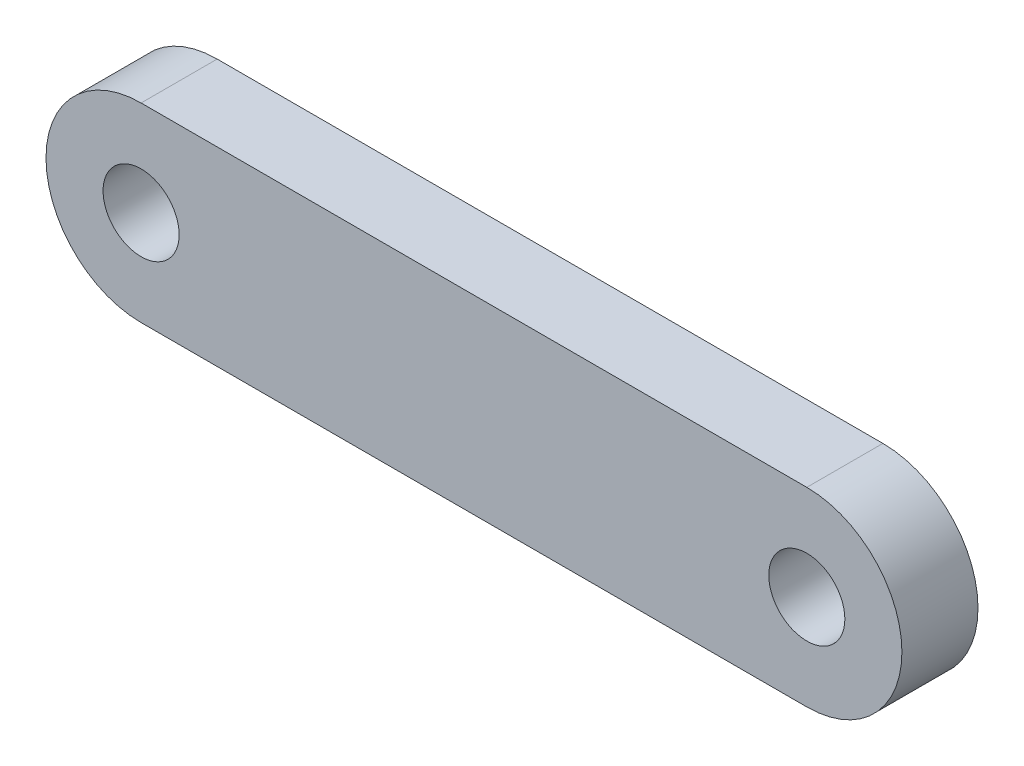
SolidWorks part; units mm, degrees
ref_plane "Front Plane" through (0, 0, 0) normal (0, 0, 1) x (1, 0, 0)
ref_plane "Top Plane" through (0, 0, 0) normal (0, 1, 0) x (1, 0, 0)
ref_plane "Right Plane" through (0, 0, 0) normal (1, 0, 0) x (0, 0, -1)
sketch "Sketch1" plane through (0, 0, 0) normal (0, 0, 1) x (1, 0, 0)
  line L0 (-35, 0) -> (0, 0) construction
  line L1 (-35, 5) -> (0, 5)
  line L2 (-35, -5) -> (0, -5)
  arc A0 (-35, 5) -> (-35, -5) centre (-35, 0) ccw
  arc A1 (0, -5) -> (0, 5) centre (0, 0) ccw
  circle A2 centre (-35, 0) radius 2
  circle A3 centre (0, 0) radius 2
  point P3 (-17.5, 0)
  point P12 (0, 0)
  dimension "D1" = 35
  dimension "D2" = 5
  dimension "D3" = 4
extrude "Boss-Extrude1" add sketch "Sketch1" along normal blind 4
